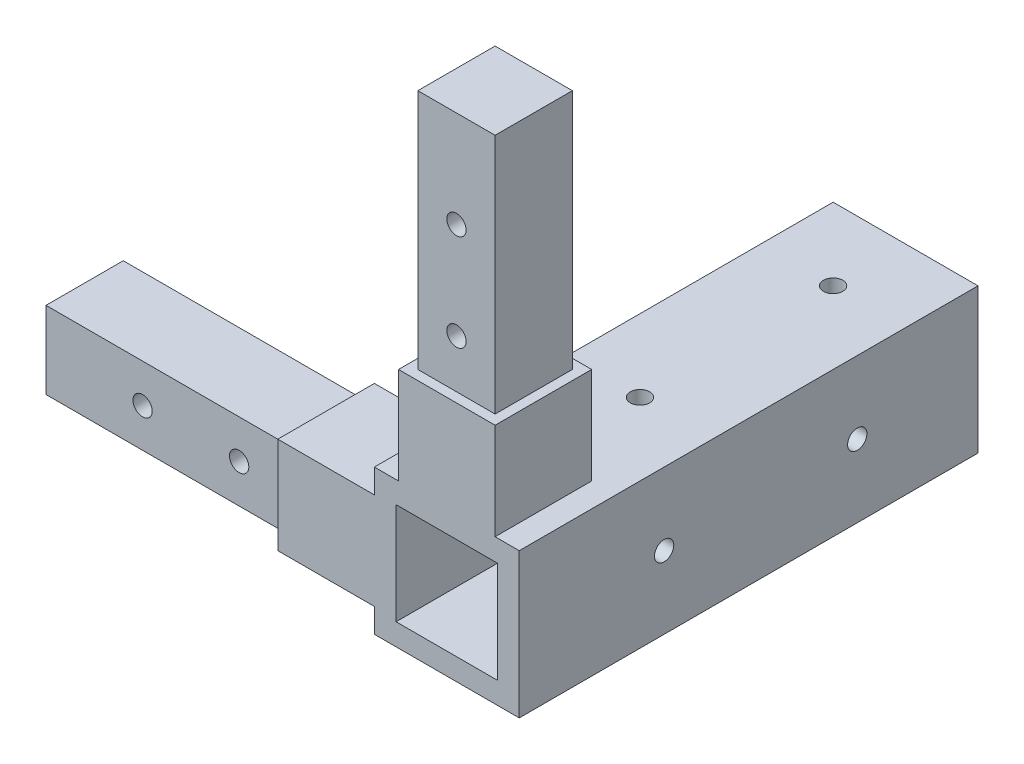
SolidWorks part; units mm, degrees
ref_plane "Front Plane" through (0, 0, 0) normal (0, 0, 1) x (1, 0, 0)
ref_plane "Top Plane" through (0, 0, 0) normal (0, 1, 0) x (1, 0, 0)
ref_plane "Right Plane" through (0, 0, 0) normal (1, 0, 0) x (0, 0, -1)
sketch "Sketch1" plane through (0, 0, 0) normal (0, 0, 1) x (1, 0, 0)
  line L1 (50, -50) -> (-50, -50)
  line L2 (50, -50) -> (50, 50)
  line L3 (50, 50) -> (-50, 50)
  line L4 (-50, -50) -> (-50, 50)
  line L5 (50, -50) -> (-50, 50) construction
  line L6 (50, 50) -> (-50, -50) construction
  point P0 (0, 0)
  dimension "D1" = 100
  dimension "D2" = 100
extrude "Boss-Extrude1" add sketch "Sketch1" against normal blind 100
sketch "Sketch5" plane through (0, 0, -100) normal (0, 0, -1) x (-1, 0, 0)
  line L0 (50, -50) -> (50, 50)
  line L1 (50, 50) -> (-50, 50)
  line L2 (-50, 50) -> (-50, -20)
  line L3 (-50, -50) -> (-50, 50) construction
  line L4 (-20, -20) -> (-50, -20)
  line L5 (50, -50) -> (-20, -50)
  line L8 (-20, -50) -> (-20, -20)
  dimension "D1" = 70
extrude "Cut-Extrude16" cut sketch "Sketch5" against normal blind 70
sketch "Sketch8" plane through (0, 0, -30) normal (0, 0, -1) x (-1, 0, 0)
  line L0 (-20, -20) -> (-20, 50)
  line L1 (50, 50) -> (-50, 50) construction
  line L2 (-20, 50) -> (50, 50)
  line L3 (50, 50) -> (50, -20)
  line L4 (50, -50) -> (50, 50) construction
  line L5 (50, -20) -> (-20, -20)
extrude "Cut-Extrude17" cut sketch "Sketch8" against normal blind 30
sketch "Sketch9" plane through (0, 0, -100) normal (0, 0, -1) x (-1, 0, 0)
  line L3 (-24.5, -45.5) -> (-45.5, -45.5)
  line L4 (-24.5, -45.5) -> (-24.5, -24.5)
  line L5 (-24.5, -24.5) -> (-45.5, -24.5)
  line L6 (-45.5, -45.5) -> (-45.5, -24.5)
  point P8 (-35, -35)
  dimension "D1" = 21
extrude "Cut-Extrude20" cut sketch "Sketch9" against normal blind 100
sketch "Sketch10" plane through (-50, 0, 0) normal (-1, 0, 0) x (0, 0, 1)
  line L3 (-23, -27) -> (-7, -27)
  line L4 (-23, -27) -> (-23, -43)
  line L5 (-23, -43) -> (-7, -43)
  line L6 (-7, -27) -> (-7, -43)
  line L9 (0, -50) -> (-30, -50)
  line L10 (0, -50) -> (0, -20)
  line L11 (0, -20) -> (-30, -20)
  line L12 (-30, -50) -> (-30, -20)
  point P8 (-15, -35)
  point P13 (-15, -35)
  dimension "D1" = 16
extrude "Cut-Extrude21" cut sketch "Sketch10" against normal blind 50
sketch "Sketch11" plane through (0, 0, 0) normal (-1, 0, 0) x (0, 0, 1)
  line L3 (-25, -25) -> (-5, -25)
  line L4 (-25, -25) -> (-25, -45)
  line L5 (-25, -45) -> (-5, -45)
  line L6 (-5, -25) -> (-5, -45)
  line L9 (0, -50) -> (-30, -50)
  line L10 (0, -50) -> (0, -20)
  line L11 (0, -20) -> (-30, -20)
  line L12 (-30, -50) -> (-30, -20)
  point P8 (-15, -35)
  point P13 (-15, -35)
  dimension "D1" = 20
extrude "Cut-Extrude22" cut sketch "Sketch11" against normal blind 20
sketch "Sketch12" plane through (0, 50, 0) normal (0, 1, 0) x (1, 0, 0)
  line L0 (20, 30) -> (50, 0) construction
  line L1 (50, 30) -> (20, 0) construction
  line L3 (25, 25) -> (45, 25)
  line L4 (25, 25) -> (25, 5)
  line L5 (25, 5) -> (45, 5)
  line L6 (45, 25) -> (45, 5)
  line L7 (25, 25) -> (45, 5) construction
  line L8 (25, 5) -> (45, 25) construction
  line L9 (20, 30) -> (50, 30)
  line L10 (20, 30) -> (20, 0)
  line L11 (20, 0) -> (50, 0)
  line L12 (50, 30) -> (50, 0)
  line L13 (20, 30) -> (50, 0) construction
  line L14 (20, 0) -> (50, 30) construction
  point P8 (35, 15)
  point P13 (35, 15)
  dimension "D1" = 20
extrude "Cut-Extrude23" cut sketch "Sketch12" against normal blind 70
sketch "Sketch13" plane through (0, 50, 0) normal (0, 1, 0) x (1, 0, 0)
  line L0 (25, 25) -> (45, 5) construction
  line L1 (45, 25) -> (25, 5) construction
  line L3 (27, 23) -> (43, 23)
  line L4 (27, 23) -> (27, 7)
  line L5 (27, 7) -> (43, 7)
  line L6 (43, 23) -> (43, 7)
  line L7 (27, 23) -> (43, 7) construction
  line L8 (27, 7) -> (43, 23) construction
  line L9 (25, 25) -> (45, 25)
  line L10 (25, 25) -> (25, 5)
  line L11 (25, 5) -> (45, 5)
  line L12 (45, 25) -> (45, 5)
  line L13 (25, 25) -> (45, 5) construction
  line L14 (25, 5) -> (45, 25) construction
  point P8 (35, 15)
  point P13 (35, 15)
  dimension "D1" = 16
extrude "Cut-Extrude24" cut sketch "Sketch13" against normal blind 50
sketch "Sketch15" plane through (0, -20, 0) normal (0, 1, 0) x (1, 0, 0)
  line L0 (35, 100) -> (35, 85) construction
  line L1 (50, 100) -> (20, 100) construction
  line L2 (35, 85) -> (35, 45) construction
  circle A0 centre (35, 85) radius 2
  circle A1 centre (35, 45) radius 2
  dimension "D2" = 40
  dimension "D1" = 15
extrude "Cut-Extrude25" cut sketch "Sketch15" against normal blind 30
sketch "Sketch16" plane through (50, 0, 0) normal (1, 0, 0) x (0, 0, -1)
  circle A0 centre (75, -35) radius 2
  circle A1 centre (35, -35) radius 2
  dimension "D2" = 40
extrude "Cut-Extrude26" cut sketch "Sketch16" against normal blind 30
sketch "Sketch17" plane through (0, 0, -23) normal (0, 0, -1) x (-1, 0, 0)
  line L2 (-35, 30) -> (-35, 10) construction
  circle A0 centre (-35, 30) radius 2
  circle A1 centre (-35, 10) radius 2
  dimension "D2" = 0
extrude "Cut-Extrude27" cut sketch "Sketch17" against normal blind 16
sketch "Sketch18" plane through (0, 0, -23) normal (0, 0, -1) x (-1, 0, 0)
  circle A0 centre (30, -35) radius 2
  circle A1 centre (10, -35) radius 2
  dimension "D2" = 20
extrude "Cut-Extrude29" cut sketch "Sketch18" against normal blind 16
sketch "Sketch19" plane through (0, 0, 0) normal (0, 0, 1) x (1, 0, 0)
  line L2 (20, -20) -> (50, -20)
  line L3 (20, -20) -> (20, -50)
  line L4 (20, -50) -> (50, -50)
  line L5 (50, -20) -> (50, -50)
  point P4 (35, -35)
extrude "Cut-Extrude30" cut sketch "Sketch19" against normal blind 5
